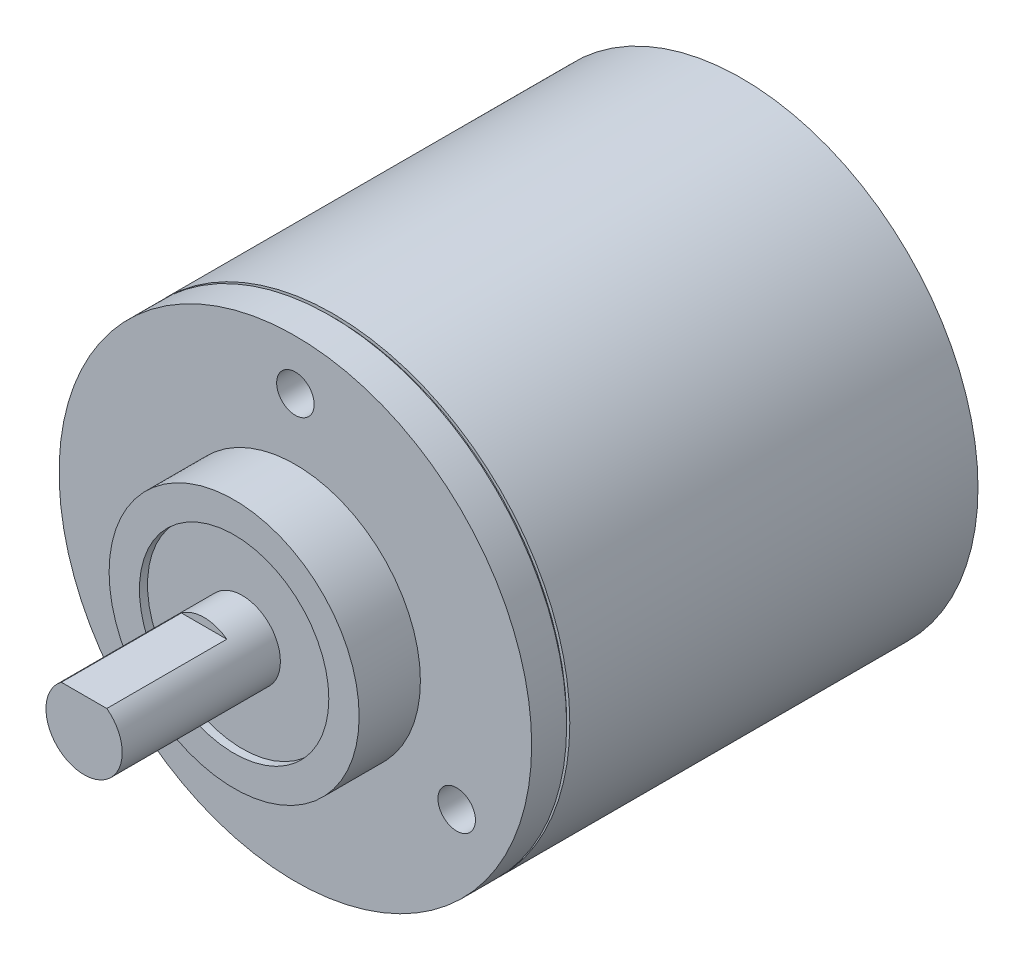
SolidWorks part; units mm, degrees
ref_plane "Plan de face" through (0, 0, 0) normal (0, 0, 1) x (1, 0, 0)
ref_plane "Plan de dessus" through (0, 0, 0) normal (0, 1, 0) x (1, 0, 0)
ref_plane "Plan de droite" through (0, 0, 0) normal (1, 0, 0) x (0, 0, -1)
sketch "Esquisse1" plane through (0, 0, 0) normal (0, 0, 1) x (1, 0, 0)
  circle A0 centre (0, 0) radius 18.9
  dimension "D1" = 37.8
extrude "Boss.-Extru.1" add sketch "Esquisse1" along normal blind 35.6 and the other way blind 0.1 contours A0
sketch "Esquisse3" plane through (0, 0, 35.6) normal (0, 0, 1) x (1, 0, 0)
  circle A0 centre (0, 0) radius 10
  dimension "D1" = 20
extrude "Boss.-Extru.3" add sketch "Esquisse3" along normal blind 4.9
sketch "Esquisse4" plane through (0, 0, 40.5) normal (0, 0, 1) x (1, 0, 0)
  circle A0 centre (0, 0) radius 3.05
  dimension "D1" = 6.1
extrude "Boss.-Extru.4" add sketch "Esquisse4" along normal blind 12
sketch "Esquisse5" plane through (0, 0, 35.6) normal (0, 0, 1) x (1, 0, 0)
  circle A0 centre (0, 14.9) radius 1.5
  circle A1 centre (0, 0) radius 10 construction
  dimension "D1" = 3
  dimension "D2" = 14.9
extrude "Enlèv. mat.-Extru.1" cut sketch "Esquisse5" against normal blind 8
sketch "Esquisse6" plane through (0, 0, 40.5) normal (0, 0, 1) x (1, 0, 0)
  circle A0 centre (0, 0) radius 7.575
  circle A1 centre (0, 0) radius 3.05
  dimension "D1" = 15.15
extrude "Enlèv. mat.-Extru.3" cut sketch "Esquisse6" against normal blind 0.65
sketch "Esquisse7" plane through (0, 0, 52.5) normal (0, 0, 1) x (1, 0, 0)
  line L0 (-4.3171, 2.45) -> (4.5179, 2.45)
  line L1 (4.5179, 2.45) -> (1.4809, 5.487)
  line L2 (1.4809, 5.487) -> (-3.3633, 5.487)
  line L3 (-3.3633, 5.487) -> (-4.3171, 2.45)
  dimension "D1" = 2.45
extrude "Enlèv. mat.-Extru.4" cut sketch "Esquisse7" against normal blind 9.6
pattern_circular "Répétition circulaire1" count 3 every 120 about axis through (0, 0, 0) along (0, 0, 1) of "Enlèv. mat.-Extru.1"
sketch "Esquisse8" plane through (0, 0, 0) normal (1, 0, 0) x (0, 0, -1)
  line L0 (-35.6, 18.9) -> (-35.6, -18.9) construction
  line L1 (-32.8, 21.8462) -> (-32.55, 21.8462)
  line L2 (-32.8, 21.8462) -> (-32.8, 18.65)
  line L3 (-32.8, 18.65) -> (-32.55, 18.65)
  line L4 (-32.55, 21.8462) -> (-32.55, 18.65)
  line L5 (0.1, 18.9) -> (-35.6, 18.9) construction
  dimension "D1" = 2.8
  dimension "D2" = 0.25
  dimension "D3" = 0.25
revolve "Enlèvement de matière-Révolution1" cut sketch "Esquisse8" angle 360 about axis through (0, 0, -0.1) along (0, 0, 1)
move or copy body "Body-Move/Copy1" [suppressed] bodies to move or copy 109
